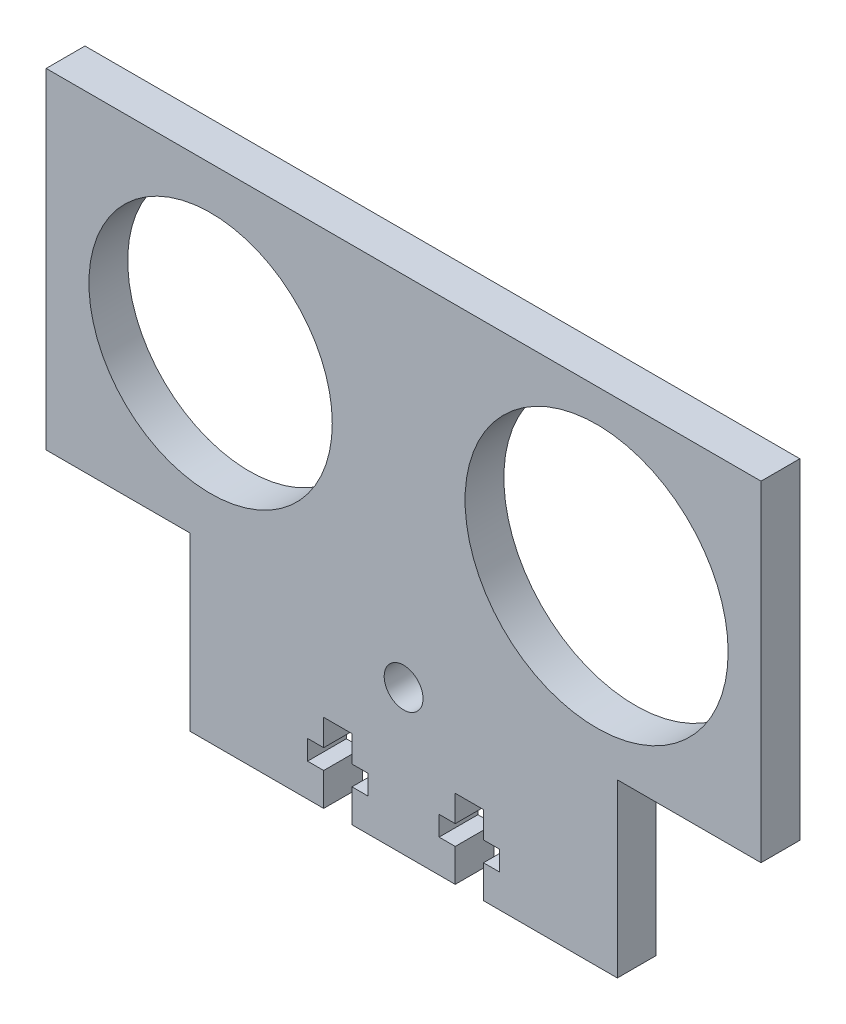
SolidWorks part; units mm, degrees
ref_plane "Front Plane" through (0, 0, 0) normal (0, 0, 1) x (1, 0, 0)
ref_plane "Top Plane" through (0, 0, 0) normal (0, 1, 0) x (1, 0, 0)
ref_plane "Right Plane" through (0, 0, 0) normal (1, 0, 0) x (0, 0, -1)
sketch "Sketch1" plane through (0, 0, 0) normal (0, 0, 1) x (1, 0, 0)
  line L0 (0, 0) -> (-29.3449, 29.3449) construction
  line L1 (0, 0) -> (0, 54.3449) construction
  line L2 (-32.5, 4.1) -> (-32.5, -22)
  line L3 (-32.5, -22) -> (32.5, -22)
  line L4 (32.5, -22) -> (32.5, 4.1)
  line L5 (0, 0) -> (0, -22) construction
  line L6 (0, 0) -> (29.3449, 29.3449) construction
  line L10 (-32.5, 4.1) -> (-54.3449, 4.1)
  line L11 (-54.3449, 4.1) -> (-54.3449, 54.3449)
  line L12 (-54.3449, 54.3449) -> (54.3449, 54.3449)
  line L13 (54.3449, 54.3449) -> (54.3449, 4.1)
  line L14 (54.3449, 4.1) -> (32.5, 4.1)
  circle A0 centre (0, 0) radius 2.95
  circle A1 centre (29.3449, 29.3449) radius 20
  circle A2 centre (-29.3449, 29.3449) radius 18.5
  dimension "D1" = 5.9
  dimension "D9" = 37
  dimension "D11" = 40
  dimension "D2" = 41.5
  dimension "D4" = 45
  dimension "D5" = 22
  dimension "D6" = 65
  dimension "D3" = 25
  dimension "D7" = 25
  dimension "D8" = 26.1
  dimension "D10" = 45
extrude "Boss-Extrude1" add sketch "Sketch1" along normal blind 5.9
sketch "Sketch3" plane through (0, 0, 5.9) normal (0, 0, 1) x (1, 0, 0)
  line L0 (-32.5, -22) -> (32.5, -22) construction
  line L1 (-12.15, -22) -> (-7.85, -22)
  line L2 (-12.15, -22) -> (-12.15, -17)
  line L3 (-12.15, -10) -> (-7.85, -10)
  line L4 (-7.85, -22) -> (-7.85, -17)
  line L5 (0, 0) -> (0, -22) construction
  line L6 (-7.85, -14) -> (-5.4, -14)
  line L7 (-14.6, -14) -> (-12.15, -14)
  line L8 (-14.6, -14) -> (-14.6, -17)
  line L9 (-14.6, -17) -> (-12.15, -17)
  line L10 (-5.4, -14) -> (-5.4, -17)
  line L11 (-12.15, -14) -> (-12.15, -10)
  line L12 (-7.85, -17) -> (-5.4, -17)
  line L13 (-7.85, -14) -> (-7.85, -10)
  line L14 (7.85, -14) -> (7.85, -10)
  line L15 (7.85, -17) -> (5.4, -17)
  line L16 (12.15, -14) -> (12.15, -10)
  line L17 (5.4, -14) -> (5.4, -17)
  line L18 (14.6, -17) -> (12.15, -17)
  line L19 (14.6, -14) -> (14.6, -17)
  line L20 (14.6, -14) -> (12.15, -14)
  line L21 (7.85, -14) -> (5.4, -14)
  line L22 (7.85, -22) -> (7.85, -17)
  line L23 (12.15, -10) -> (7.85, -10)
  line L24 (12.15, -22) -> (12.15, -17)
  line L25 (12.15, -22) -> (7.85, -22)
  point P6 (-10, -10)
  point P18 (-13.375, -17)
  dimension "D1" = 4.3
  dimension "D2" = 10
  dimension "D3" = 12
  dimension "D4" = 9.2
  dimension "D5" = 3
  dimension "D6" = 5
extrude "Cut-Extrude2" cut sketch "Sketch3" against normal through all
equation "\"smallPulleyTeeth\"= 15"
equation "\"largePulleyTeeth\"= 30"
equation "\"eighthThick\"= 2.9mm"
equation "\"sixteenthThick\"= 1.7mm"
equation "\"quarterThick\"=5.9mm"
equation "\"OD\"= 145mm"
equation "\"puckAngle\"= 60.5deg"
equation "\"puckDiam\"= 76.5mm"
equation "\"axlePress\"= 5.9mm"
equation "\"D1@Sketch1\"=\"axlePress\""
equation "\"D1@Boss-Extrude1\"=\"quarterThick\""
equation "\"press\"= 0.2mm"
equation "\"wheelClear\"= 0.3mm"
equation "\"10-32clear\"= 4.5mm"
equation "\"D1@Sketch3\"=\"10-32clear\"-\"press\""
equation "\"6-32clear\"= 3.3mm"
equation "\"8-32clear\"= 4.0mm"
equation "\"wheelHeight\"= 22mm"
equation "\"D5@Sketch1\"=\"wheelHeight\""
equation "\"D8@Sketch1\"=\"eighthThick\"*9"
equation "\"4-40clear\"= 2.55mm"
equation "\"wheelWell\"= 65mm"
equation "\"D6@Sketch1\"=\"wheelWell\""
